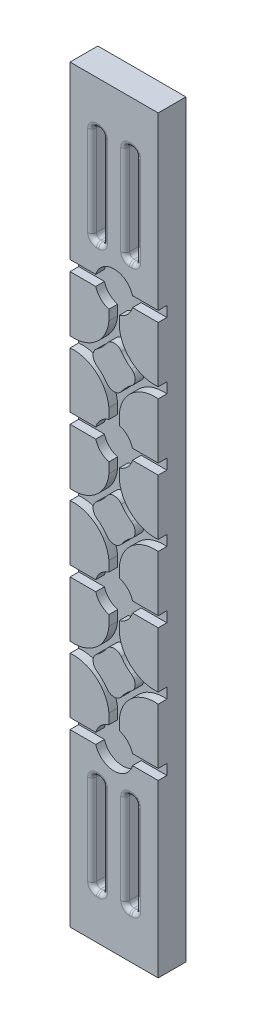
SolidWorks part; units mm, degrees
ref_plane "Front Plane" through (0, 0, 0) normal (0, 0, 1) x (1, 0, 0)
ref_plane "Top Plane" through (0, 0, 0) normal (0, 1, 0) x (1, 0, 0)
ref_plane "Right Plane" through (0, 0, 0) normal (1, 0, 0) x (0, 0, -1)
sketch "Sketch1" plane through (0, 0, 0) normal (0, 0, 1) x (1, 0, 0)
  line L1 (0, 0) -> (25.4, 0)
  line L2 (0, 0) -> (0, 215.9)
  line L3 (0, 215.9) -> (25.4, 215.9)
  line L4 (25.4, 0) -> (25.4, 215.9)
  line L5 (6.35, 203.2) -> (9.525, 203.2)
  line L6 (6.35, 203.2) -> (6.35, 174.625)
  line L7 (6.35, 174.625) -> (9.525, 174.625)
  line L8 (9.525, 203.2) -> (9.525, 174.625)
  line L9 (15.875, 203.2) -> (19.05, 203.2)
  line L10 (15.875, 203.2) -> (15.875, 174.625)
  line L11 (15.875, 174.625) -> (19.05, 174.625)
  line L12 (19.05, 203.2) -> (19.05, 174.625)
  line L13 (6.35, 41.275) -> (9.525, 41.275)
  line L14 (6.35, 41.275) -> (6.35, 12.7)
  line L15 (6.35, 12.7) -> (9.525, 12.7)
  line L16 (9.525, 41.275) -> (9.525, 12.7)
  line L17 (15.875, 41.275) -> (19.05, 41.275)
  line L18 (15.875, 41.275) -> (15.875, 12.7)
  line L19 (15.875, 12.7) -> (19.05, 12.7)
  line L20 (19.05, 41.275) -> (19.05, 12.7)
  dimension "D1" = 25.4
  dimension "D2" = 215.9
  dimension "D3" = 6.35
  dimension "D4" = 6.35
  dimension "D5" = 3.175
  dimension "D6" = 12.7
  dimension "D7" = 28.575
  dimension "D8" = 28.575
  dimension "D9" = 12.7
extrude "Boss-Extrude1" add sketch "Sketch1" along normal blind 8
fillet "Fillet1" radius 1.27 48 edges at (17.4625, 41.275, 8) (17.4625, 41.275, 0) (7.9375, 41.275, 8) (7.9375, 41.275, 0) (19.05, 26.9875, 8) (19.05, 26.9875, 0) (9.525, 26.9875, 8) (9.525, 26.9875, 0) (17.4625, 203.2, 8) (17.4625, 203.2, 0) (7.9375, 203.2, 8) (7.9375, 203.2, 0) (19.05, 188.9125, 8) (19.05, 188.9125, 0) (9.525, 188.9125, 8) (9.525, 188.9125, 0) (15.875, 26.9875, 8) (15.875, 41.275, 4) (15.875, 26.9875, 0) (6.35, 26.9875, 8) (6.35, 41.275, 4) (6.35, 26.9875, 0) (19.05, 12.7, 4) (17.4625, 12.7, 8) (15.875, 12.7, 4) (17.4625, 12.7, 0) (9.525, 12.7, 4) (7.9375, 12.7, 8) (6.35, 12.7, 4) (7.9375, 12.7, 0) (15.875, 188.9125, 8) (15.875, 203.2, 4) (15.875, 188.9125, 0) (6.35, 188.9125, 8) (6.35, 203.2, 4) (6.35, 188.9125, 0) (19.05, 174.625, 4) (17.4625, 174.625, 8) (15.875, 174.625, 4) (17.4625, 174.625, 0) (9.525, 174.625, 4) (7.9375, 174.625, 8) (6.35, 174.625, 4) (7.9375, 174.625, 0) (9.525, 203.2, 4) (9.525, 41.275, 4) (19.05, 41.275, 4) (19.05, 203.2, 4)
sketch "Sketch2" plane through (0, 0, 8) normal (0, 0, 1) x (1, 0, 0)
  line L0 (12.7, 215.9) -> (12.7, 165.1) construction
  line L1 (25.4, 215.9) -> (0, 215.9) construction
  line L2 (25.4, 0) -> (25.4, 215.9) construction
  line L3 (17.9915, 166.6) -> (25.4, 166.6)
  line L5 (17.9915, 163.6) -> (25.4, 163.6)
  line L6 (25.4, 166.6) -> (25.4, 163.6)
  line L7 (0, 215.9) -> (0, 0) construction
  line L8 (7.4085, 166.6) -> (0, 166.6)
  line L10 (7.4085, 163.6) -> (0, 163.6)
  line L11 (0, 166.6) -> (0, 163.6)
  line L12 (17.9915, 128.5) -> (25.4, 128.5)
  line L13 (17.9915, 125.5) -> (25.4, 125.5)
  line L14 (25.4, 128.5) -> (25.4, 125.5)
  line L15 (7.4085, 128.5) -> (0, 128.5)
  line L16 (7.4085, 125.5) -> (0, 125.5)
  line L17 (0, 128.5) -> (0, 125.5)
  line L18 (17.9915, 90.4) -> (25.4, 90.4)
  line L19 (17.9915, 87.4) -> (25.4, 87.4)
  line L20 (25.4, 90.4) -> (25.4, 87.4)
  line L21 (7.4085, 90.4) -> (0, 90.4)
  line L22 (7.4085, 87.4) -> (0, 87.4)
  line L23 (0, 90.4) -> (0, 87.4)
  line L24 (17.9915, 52.3) -> (25.4, 52.3)
  line L25 (17.9915, 49.3) -> (25.4, 49.3)
  line L26 (25.4, 52.3) -> (25.4, 49.3)
  line L27 (7.4085, 52.3) -> (0, 52.3)
  line L28 (7.4085, 49.3) -> (0, 49.3)
  line L29 (0, 52.3) -> (0, 49.3)
  line L30 (25.4, 128.5) -> (25.4, 163.6) construction
  line L31 (11.2, 159.8085) -> (14.2, 159.8085) construction
  line L32 (11.2, 159.8085) -> (11.2, 156.8726)
  line L33 (11.2, 156.8085) -> (14.2, 156.8085) construction
  line L34 (14.2, 159.8085) -> (14.2, 156.8726)
  line L35 (12.7, 156.8085) -> (12.7, 159.8085) construction
  line L36 (25.4, 147.5559) -> (27.4, 147.5559)
  line L37 (27.4, 147.5559) -> (27.4, 144.5441)
  line L38 (25.4, 109.4559) -> (27.4, 109.4559)
  line L39 (0, 128.5) -> (0, 163.6) construction
  line L40 (27.4, 109.4559) -> (27.4, 106.4441)
  line L41 (-2, 147.5559) -> (-2, 144.5441)
  line L42 (0, 147.5559) -> (-2, 147.5559)
  line L43 (14.2, 132.2915) -> (14.2, 135.2274)
  line L44 (11.2, 132.2915) -> (11.2, 135.2274)
  line L45 (11.1941, 135.2915) -> (14.2059, 135.2915) construction
  line L46 (0, 144.5441) -> (-2, 144.5441)
  line L47 (25.4, 144.5441) -> (27.4, 144.5441)
  line L48 (-2, 109.4559) -> (-2, 106.4441)
  line L49 (0, 109.4559) -> (-2, 109.4559)
  line L50 (0, 106.4441) -> (-2, 106.4441)
  line L51 (25.4, 106.4441) -> (27.4, 106.4441)
  line L52 (11.2, 118.7085) -> (14.2, 118.7085) construction
  line L53 (11.1941, 97.1915) -> (14.2059, 97.1915) construction
  line L54 (14.2, 94.1915) -> (14.2, 97.1274)
  line L55 (11.2, 94.1915) -> (11.2, 97.1274)
  line L56 (14.2, 121.7085) -> (14.2, 118.7726)
  line L57 (11.2, 121.7085) -> (11.2, 118.7726)
  line L58 (25.4, 71.3559) -> (27.4, 71.3559)
  line L59 (27.4, 71.3559) -> (27.4, 68.3441)
  line L60 (-2, 71.3559) -> (-2, 68.3441)
  line L61 (0, 71.3559) -> (-2, 71.3559)
  line L62 (0, 68.3441) -> (-2, 68.3441)
  line L63 (25.4, 68.3441) -> (27.4, 68.3441)
  line L64 (11.2, 80.6085) -> (14.2, 80.6085) construction
  line L65 (11.1941, 59.0915) -> (14.2059, 59.0915) construction
  line L66 (14.2, 56.0915) -> (14.2, 59.0274)
  line L67 (11.2, 56.0915) -> (11.2, 59.0274)
  line L68 (14.2, 83.6085) -> (14.2, 80.6726)
  line L69 (11.2, 83.6085) -> (11.2, 80.6726)
  line L78 (0, 53.2848) -> (0, 88.3848) construction
  line L82 (25.4, 109.9483) -> (27.4, 109.9483) [skipped]
  line L83 (27.4, 109.9483) -> (27.4, 106.9365) [skipped]
  line L86 (-2, 109.9483) -> (-2, 106.9365) [skipped]
  line L87 (0, 109.9483) -> (-2, 109.9483) [skipped]
  line L88 (0, 106.9365) -> (-2, 106.9365) [skipped]
  line L89 (25.4, 106.9365) -> (27.4, 106.9365) [skipped]
  line L90 (14.2, 94.6577) -> (14.2, 97.6198) [skipped]
  line L91 (11.2, 94.6587) -> (11.2, 97.6839) [skipped]
  line L92 (25.4, 90.8924) -> (25.4, 125.9924) construction
  line L93 (0, 90.8924) -> (0, 125.9924) construction
  line L94 (11.1941, 97.6839) -> (14.2059, 97.6839) construction
  line L95 (11.2, 119.2009) -> (14.2, 119.2009) construction
  line L96 (11.2, 122.1747) -> (11.2, 119.265) [skipped]
  line L97 (14.2, 122.1747) -> (14.2, 119.265) [skipped]
  line L98 (12.7, 119.2009) -> (12.7, 122.2009) construction
  line L100 (-2, 72.3407) -> (-2, 69.3289) [skipped]
  line L101 (0, 72.3407) -> (-2, 72.3407) [skipped]
  line L102 (0, 69.3289) -> (-2, 69.3289) [skipped]
  line L103 (11.2, 81.5933) -> (14.2, 81.5933) construction
  line L104 (11.1941, 60.0763) -> (14.2059, 60.0763) construction
  line L105 (14.2, 84.6047) -> (14.2, 81.5935) [skipped]
  line L106 (12.7, 81.5933) -> (12.7, 84.5933) construction
  line L107 (11.2, 84.6047) -> (11.2, 81.5935) [skipped]
  line L108 (14.2, 57.0877) -> (14.2, 60.0765) [skipped]
  line L109 (11.2, 57.0877) -> (11.2, 60.0765) [skipped]
  line L110 (25.4, 72.3407) -> (27.4, 72.3407) [skipped]
  line L111 (27.4, 72.3407) -> (27.4, 69.3289) [skipped]
  line L113 (25.4, 69.3289) -> (27.4, 69.3289) [skipped]
  line L114 (25.4, 53.2848) -> (25.4, 88.3848) construction
  arc A0 (7.4085, 163.6) -> (11.2, 159.8085) centre (12.7, 165.1) ccw
  arc A1 (17.9915, 166.6) -> (7.4085, 166.6) centre (12.7, 165.1) ccw
  arc A2 (7.4085, 125.5) -> (11.2, 121.7085) centre (12.7, 127) ccw
  arc A3 (17.9915, 128.5) -> (14.2, 132.2915) centre (12.7, 127) ccw
  arc A4 (7.4085, 87.4) -> (11.2, 83.6085) centre (12.7, 88.9) ccw
  arc A5 (17.9915, 90.4) -> (14.2, 94.1915) centre (12.7, 88.9) ccw
  arc A6 (7.4085, 49.3) -> (17.9915, 49.3) centre (12.7, 50.8) ccw
  arc A7 (17.9915, 52.3) -> (14.2, 56.0915) centre (12.7, 50.8) ccw
  arc A8 (23.4585, 146.05) -> (12.7, 156.8085) centre (24.4292, 157.7793) cw
  arc A9 (25.4, 147.5559) -> (14.2, 156.8726) centre (24.4292, 157.7793) cw
  arc A10 (25.5418, 146.0626) -> (12.7, 156.8085) centre (24.4292, 157.7793) cw construction
  arc A11 (0, 147.5559) -> (11.2, 156.8726) centre (0.9708, 157.7793) ccw
  arc A12 (1.9415, 146.05) -> (12.7, 156.8085) centre (0.9708, 157.7793) ccw
  arc A13 (14.2, 159.8085) -> (17.9915, 163.6) centre (12.7, 165.1) ccw
  arc A14 (1.9415, 146.05) -> (12.7, 135.2915) centre (0.9708, 134.3207) cw
  arc A15 (0, 144.5441) -> (11.2, 135.2274) centre (0.9708, 134.3207) cw
  arc A16 (25.4, 144.5441) -> (14.2, 135.2274) centre (24.4292, 134.3207) ccw
  arc A17 (23.4585, 146.05) -> (12.7, 135.2915) centre (24.4292, 134.3207) ccw
  arc A18 (11.2, 132.2915) -> (7.4085, 128.5) centre (12.7, 127) ccw
  arc A20 (23.4585, 107.95) -> (12.7, 118.7085) centre (24.4292, 119.6793) cw
  arc A21 (25.4, 109.4559) -> (14.2, 118.7726) centre (24.4292, 119.6793) cw
  arc A24 (0, 109.4559) -> (11.2, 118.7726) centre (0.9708, 119.6793) ccw
  arc A25 (1.9415, 107.95) -> (12.7, 118.7085) centre (0.9708, 119.6793) ccw
  arc A28 (1.9415, 107.95) -> (12.7, 97.1915) centre (0.9708, 96.2207) cw
  arc A29 (0, 106.4441) -> (11.2, 97.1274) centre (0.9708, 96.2207) cw
  arc A32 (25.4, 106.4441) -> (14.2, 97.1274) centre (24.4292, 96.2207) ccw
  arc A33 (23.4585, 107.95) -> (12.7, 97.1915) centre (24.4292, 96.2207) ccw
  arc A35 (23.4585, 69.85) -> (12.7, 80.6085) centre (24.4292, 81.5793) cw
  arc A36 (25.4, 147.5559) -> (14.1949, 156.9322) centre (24.4292, 157.7793) cw construction
  arc A37 (25.4, 108.4424) -> (12.7, 119.2009) centre (24.4292, 120.1716) cw [skipped]
  arc A38 (25.4, 109.9483) -> (14.2, 119.265) centre (24.4292, 120.1716) cw [skipped]
  arc A39 (0, 109.9483) -> (11.2, 119.265) centre (0.9708, 120.1716) ccw [skipped]
  arc A40 (0, 108.4424) -> (12.7, 119.2009) centre (0.9708, 120.1716) ccw [skipped]
  arc A41 (0, 108.4424) -> (12.7, 97.6839) centre (0.9708, 96.7131) cw [skipped]
  arc A42 (0, 106.9365) -> (11.2051, 97.5602) centre (0.9708, 96.7131) cw [skipped]
  arc A43 (25.4, 106.9365) -> (14.1949, 97.5602) centre (24.4292, 96.7131) ccw [skipped]
  arc A44 (25.4, 108.4424) -> (12.7, 97.6839) centre (24.4292, 96.7131) ccw [skipped]
  arc A45 (25.4, 70.8348) -> (12.7, 81.5933) centre (24.4292, 82.564) cw [skipped]
  arc A46 (25.4, 72.3407) -> (14.1949, 81.717) centre (24.4292, 82.564) cw [skipped]
  arc A47 (0, 72.3407) -> (11.2051, 81.717) centre (0.9708, 82.564) ccw [skipped]
  arc A48 (0, 70.8348) -> (12.7, 81.5933) centre (0.9708, 82.564) ccw [skipped]
  arc A49 (0, 70.8348) -> (12.7, 60.0763) centre (0.9708, 59.1055) cw [skipped]
  arc A50 (0, 69.3289) -> (11.2051, 59.9525) centre (0.9708, 59.1055) cw [skipped]
  arc A51 (25.4, 69.3289) -> (14.1949, 59.9525) centre (24.4292, 59.1055) ccw [skipped]
  arc A52 (25.4, 70.8348) -> (12.7, 60.0763) centre (24.4292, 59.1055) ccw [skipped]
  arc A53 (25.4, 71.3559) -> (14.2, 80.6726) centre (24.4292, 81.5793) cw
  arc A54 (0, 71.3559) -> (11.2, 80.6726) centre (0.9708, 81.5793) ccw
  arc A55 (1.9415, 69.85) -> (12.7, 80.6085) centre (0.9708, 81.5793) ccw
  arc A56 (1.9415, 69.85) -> (12.7, 59.0915) centre (0.9708, 58.1207) cw
  arc A57 (0, 68.3441) -> (11.2, 59.0274) centre (0.9708, 58.1207) cw
  arc A58 (25.4, 68.3441) -> (14.2, 59.0274) centre (24.4292, 58.1207) ccw
  arc A59 (23.4585, 69.85) -> (12.7, 59.0915) centre (24.4292, 58.1207) ccw
  arc A60 (14.2, 121.7085) -> (17.9915, 125.5) centre (12.7, 127) ccw
  arc A61 (11.2, 94.1915) -> (7.4085, 90.4) centre (12.7, 88.9) ccw
  arc A62 (14.2, 83.6085) -> (17.9915, 87.4) centre (12.7, 88.9) ccw
  arc A63 (11.2, 56.0915) -> (7.4085, 52.3) centre (12.7, 50.8) ccw
  point P1 (0, 165.1)
  point P17 (25.4, 165.1)
  dimension "D1" = 11
  dimension "D9" = 11.7694
  dimension "D2" = 50.8
  dimension "D3" = 3
  dimension "D5" = 38.1
  dimension "D6" = 3
  dimension "D7" = 3
  dimension "D10" = 3
  dimension "D8" = 1.5
  dimension "D4" = 4
  dimension "D11" = 3
extrude "Cut-Extrude1" cut sketch "Sketch2" against normal blind 2.5
fillet "Fillet2" radius 2.54 12 edges at (12.7, 59.0915, 6.75) (1.9415, 69.85, 6.75) (23.4585, 69.85, 6.75) (12.7, 80.6085, 6.75) (12.7, 97.1915, 6.75) (1.9415, 107.95, 6.75) (23.4585, 107.95, 6.75) (12.7, 118.7085, 6.75) (23.4585, 146.05, 6.75) (12.7, 135.2915, 6.75) (1.9415, 146.05, 6.75) (12.7, 156.8085, 6.75)
